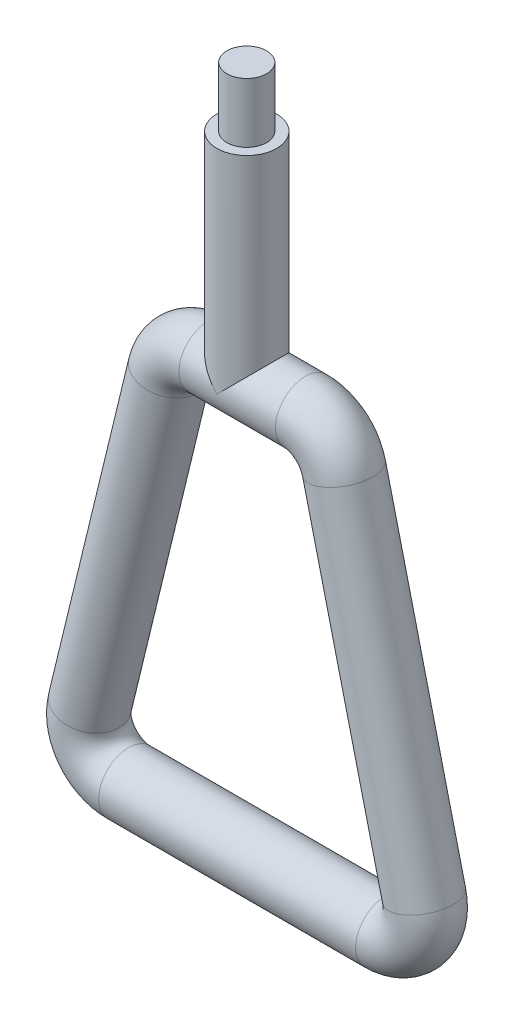
SolidWorks part; units mm, degrees
ref_plane "Front Plane" through (0, 0, 0) normal (0, 0, 1) x (1, 0, 0)
ref_plane "Top Plane" through (0, 0, 0) normal (0, 1, 0) x (1, 0, 0)
ref_plane "Right Plane" through (0, 0, 0) normal (1, 0, 0) x (0, 0, -1)
sketch "Sketch1" plane through (0, 0, 0) normal (0, 0, 1) x (1, 0, 0)
  line L0 (-9.5687, 51.5) -> (14.7049, 51.5)
  line L1 (24.4228, 43.8587) -> (44.5684, -39.1413)
  line L2 (34.8506, -51.5) -> (-29.7144, -51.5)
  line L3 (-39.4322, -39.1413) -> (-19.2866, 43.8587)
  arc A0 (-29.7144, -51.5) -> (-39.4322, -39.1413) centre (-29.7144, -41.5) cw
  arc A1 (44.5684, -39.1413) -> (34.8506, -51.5) centre (34.8506, -41.5) cw
  arc A2 (14.7049, 51.5) -> (24.4228, 43.8587) centre (14.7049, 41.5) cw
  arc A3 (-9.5687, 51.5) -> (-19.2866, 43.8587) centre (-9.5687, 41.5) ccw
  point P7 (-42.4319, -51.5)
  point P10 (47.5681, -51.5)
  point P13 (22.5681, 51.5)
  point P16 (-17.4319, 51.5)
  dimension "D7" = 10
  dimension "D1" = 90
  dimension "D2" = 40
  dimension "D3" = 103
  dimension "D4" = 51.5
  dimension "D5" = 25
  dimension "D6" = 22.5681
sweep "Sweep1" add path "Sketch1" circular profile diameter 15 parameters "D3"=15
ref_plane "Plane1" through (0, 120, 0) normal (0, 1, 0) x (1, 0, 0)
sketch "Sketch10" plane through (0, 120, 0) normal (0, 1, 0) x (1, 0, 0)
  circle A0 centre (0, 0) radius 7.5
  dimension "D1" = 15
extrude "Boss-Extrude1" add sketch "Sketch10" against normal up to surface (68.5 mm away)
sketch "Sketch11" plane through (0, 120, 0) normal (0, 1, 0) x (1, 0, 0)
  circle A0 centre (0, 0) radius 5
  circle A1 centre (0, 0) radius 7.5 construction
  circle A2 centre (0, 0) radius 7.5
  dimension "D1" = 10
extrude "Cut-Extrude1" cut sketch "Sketch11" against normal blind 15
